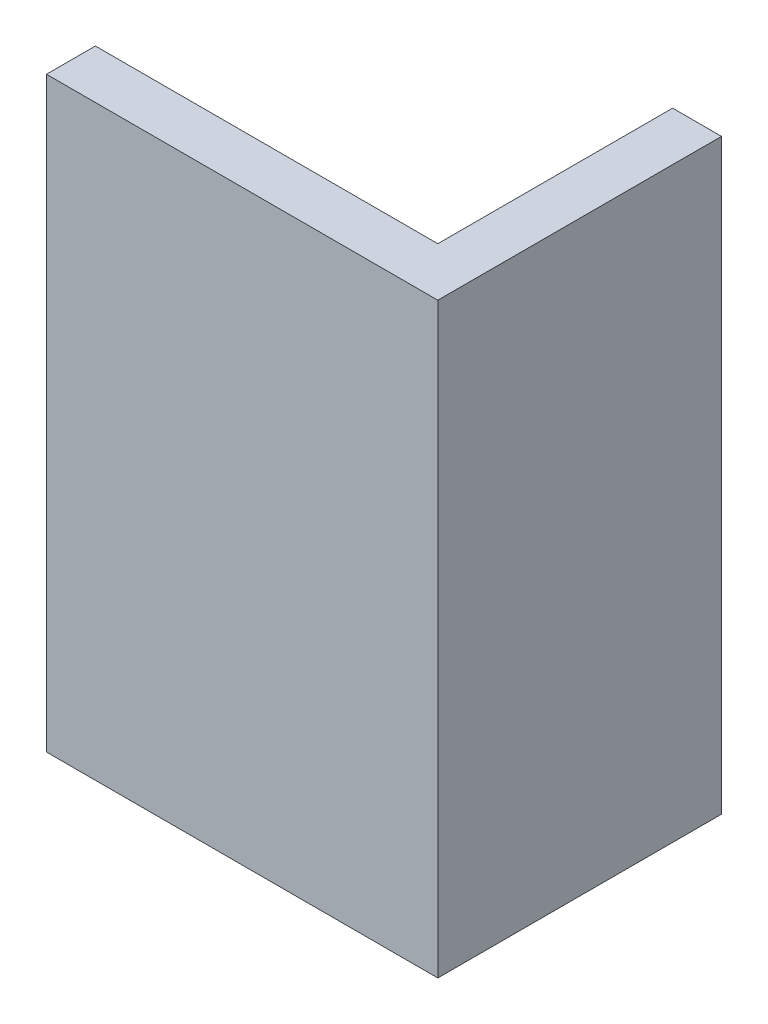
SolidWorks part; units mm, degrees
ref_plane "Front Plane" through (0, 0, 0) normal (0, 0, 1) x (1, 0, 0)
ref_plane "Top Plane" through (0, 0, 0) normal (0, 1, 0) x (1, 0, 0)
ref_plane "Right Plane" through (0, 0, 0) normal (1, 0, 0) x (0, 0, -1)
sketch "Sketch1" plane through (0, 0, 0) normal (0, 1, 0) x (1, 0, 0)
  line L0 (0, 0) -> (0, 18.415)
  line L1 (0, 18.415) -> (-3.175, 18.415)
  line L2 (-3.175, 18.415) -> (-3.175, 3.175)
  line L3 (-3.175, 3.175) -> (-25.4, 3.175)
  line L4 (-25.4, 3.175) -> (-25.4, 0)
  line L5 (-25.4, 0) -> (0, 0)
  dimension "D1" = 25.4
  dimension "D2" = 3.175
  dimension "D3" = 22.225
  dimension "D4" = 15.24
extrude "Boss-Extrude1" add sketch "Sketch1" along normal blind 38.1
sketch "Sketch4" plane through (-3.175, 0, 0) normal (-1, 0, 0) x (0, 0, 1)
  line L0 (0, 38.1) -> (-18.415, 38.1) construction
  line L1 (-3.429, 13.208) -> (-15.113, 13.208) construction
  line L2 (-3.429, 13.208) -> (-3.429, 24.892) construction
  line L3 (-3.429, 24.892) -> (-15.113, 24.892) construction
  line L4 (-15.113, 13.208) -> (-15.113, 24.892) construction
  line L5 (-3.429, 13.208) -> (-15.113, 24.892) construction
  line L6 (-3.429, 24.892) -> (-15.113, 13.208) construction
  line L7 (0, 0) -> (-18.415, 0) construction
  line L8 (-18.415, 38.1) -> (-18.415, 0) construction
  circle A0 centre (-9.271, 19.05) radius 4.6888
  circle A1 centre (76.7458, 18.1065) radius 4.445
  point P0 (-9.271, 19.05)
  dimension "D4" = 9.3776
  dimension "D5" = 8.89
  dimension "D1" = 13.208
  dimension "D2" = 13.208
  dimension "D3" = 3.302
